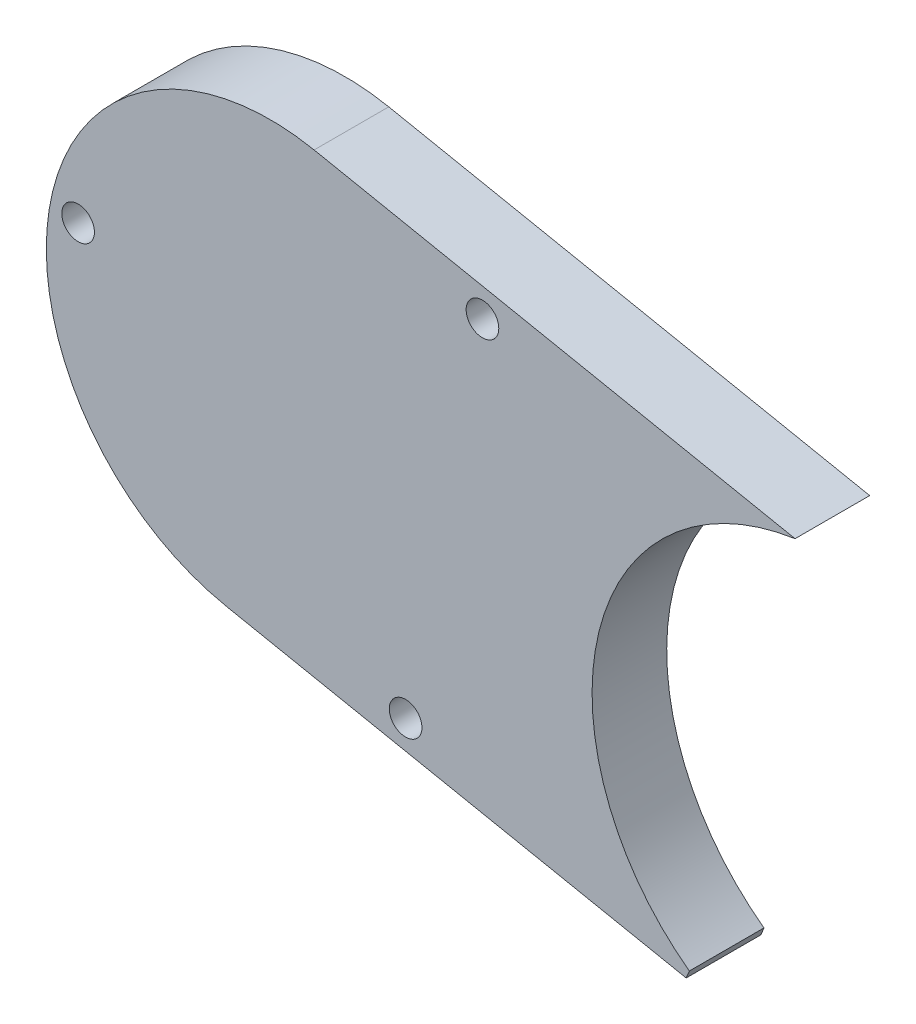
SolidWorks part; units mm, degrees
ref_plane "Front Plane" through (0, 0, 0) normal (0, 0, 1) x (1, 0, 0)
ref_plane "Top Plane" through (0, 0, 0) normal (0, 1, 0) x (1, 0, 0)
ref_plane "Right Plane" through (0, 0, 0) normal (1, 0, 0) x (0, 0, -1)
sketch "Sketch1" plane through (0, 0, 0) normal (0, 0, 1) x (1, 0, 0)
  line L0 (0, 0) -> (-30, 6) construction
  line L1 (-30, 6) -> (0, 6) construction
  line L2 (-27.6466, 17.767) -> (-1.8714, 12.6119)
  line L3 (-32.3534, -5.767) -> (-6.5781, -10.922)
  line L4 (-40.2961, 8.0592) -> (-30, 6) construction
  line L5 (-5.0331, 11.7146) -> (-33.6374, 17.4354) construction
  line L6 (-9.1515, -8.8776) -> (-37.7559, -3.1568) construction
  line L7 (-18.6253, 14.433) -> (-22.7437, -6.1592) construction
  circle A0 centre (-30, 6) radius 8 construction
  circle A1 centre (-30, 6) radius 9 construction
  arc A2 (-27.6466, 17.767) -> (-32.3534, -5.767) centre (-30, 6) ccw construction
  arc A3 (-27.6466, 17.767) -> (-32.3534, -5.767) centre (-30, 6) ccw
  circle A4 centre (0, 0) radius 18.75 construction
  arc A5 (-1.8714, 12.6119) -> (-6.5781, -10.922) centre (0, 0) ccw construction
  arc A6 (-1.8714, 12.6119) -> (-6.5781, -10.922) centre (0, 0) ccw
  circle A7 centre (-30, 6) radius 10.5 construction
  circle A8 centre (-40.2961, 8.0592) radius 0.875
  circle A9 centre (-18.6253, 14.433) radius 0.875
  circle A10 centre (-22.7437, -6.1592) radius 0.875
  dimension "D3" = 16
  dimension "D4" = 1
  dimension "D5" = 3
  dimension "D6" = 25.5
  dimension "D7" = 6
  dimension "D8" = 1.5
  dimension "D9" = 1.75
  dimension "D11" = 1.75
  dimension "D1" = 6
  dimension "D2" = 30
  dimension "D10" = 1.5
  dimension "D12" = 20
extrude "Boss-Extrude1" add sketch "Sketch1" along normal blind 4
sketch "Sketch2" plane through (0, 0, 0) normal (0, 0, -1) x (-1, 0, 0)
  line L0 (7.1923, -9.4615) -> (7.9615, -11.3077)
  line L1 (7.9615, -11.3077) -> (6.1154, -12.0769)
  line L2 (6.1154, -12.0769) -> (5.3462, -10.2308)
  line L3 (5.3462, -10.2308) -> (7.1923, -9.4615)
  line L4 (7.9615, -11.3077) -> (7.8048, -10.9316) construction
  line L5 (2.4231, -13.6154) -> (7.9615, -11.3077) construction
  dimension "D1" = 2
  dimension "D2" = 2
extrude "Cut-Extrude1" cut sketch "Sketch2" against normal blind 10
